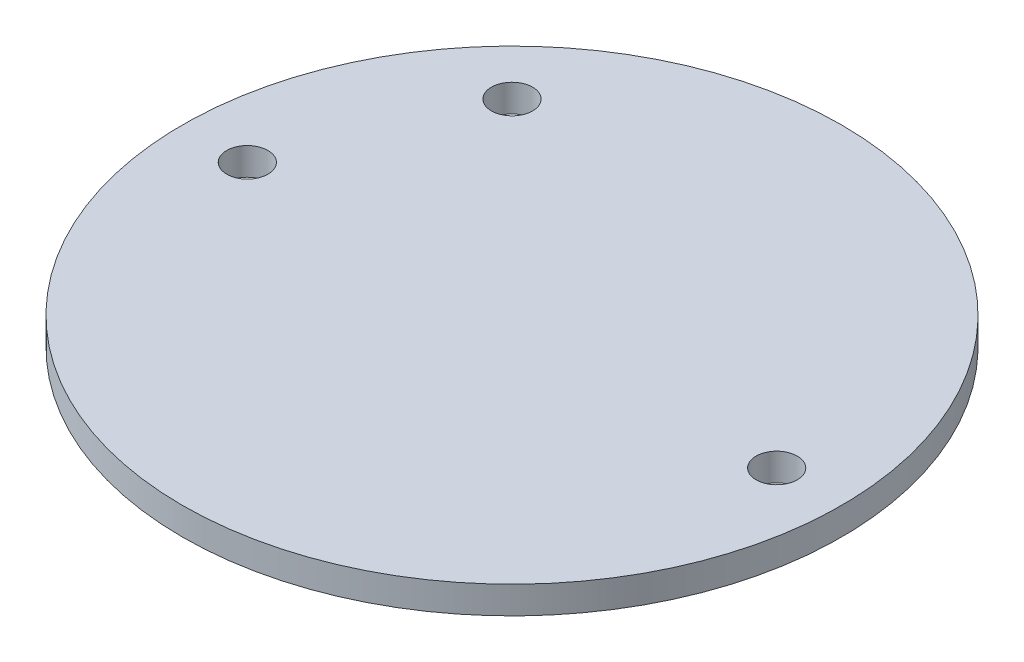
SolidWorks part; units mm, degrees
ref_plane "Front Plane" through (0, 0, 0) normal (0, 0, 1) x (1, 0, 0)
ref_plane "Top Plane" through (0, 0, 0) normal (0, 1, 0) x (1, 0, 0)
ref_plane "Right Plane" through (0, 0, 0) normal (1, 0, 0) x (0, 0, -1)
sketch "Sketch1" plane through (0, 0, 0) normal (0, 1, 0) x (1, 0, 0)
  line L0 (0, 0) -> (0, 24)
  line L1 (0, 0) -> (-13.6295, 13.6295)
  circle A0 centre (0, 0) radius 24
  circle A1 centre (-19.275, 0) radius 1.5
  circle A2 centre (19.275, 0) radius 1.5
  circle A3 centre (-13.6295, 13.6295) radius 1.5
  dimension "D1" = 48
  dimension "D3" = 3
  dimension "D5" = 3
  dimension "D8" = 3
  dimension "D2" = 19.275
  dimension "D4" = 19.275
  dimension "D6" = 45
  dimension "D7" = 19.275
extrude "Boss-Extrude1" add sketch "Sketch1" along normal blind 2
equation "\"TubeInnerDiameter\"= 48mm"
equation "\"MotorCasingDiameter\"= 29.1mm"
equation "\"TopBoltDiameter\"= 3mm"
equation "\"PressureChannelWidth\"= 8mm"
equation "\"D2@Sketch1\"=(\"TubeInnerDiameter\"/2+\"MotorCasingDiameter\"/2)/2"
equation "\"D3@Sketch1\"=\"TopBoltDiameter\""
equation "\"D4@Sketch1\"=(\"TubeInnerDiameter\"/2+\"MotorCasingDiameter\"/2)/2"
equation "\"D5@Sketch1\"=\"TopBoltDiameter\""
equation "\"D7@Sketch1\"=(\"TubeInnerDiameter\"/2+\"MotorCasingDiameter\"/2)/2"
equation "\"Height\"= 2mm"
equation "\"D1@Boss-Extrude1\"=\"Height\""
